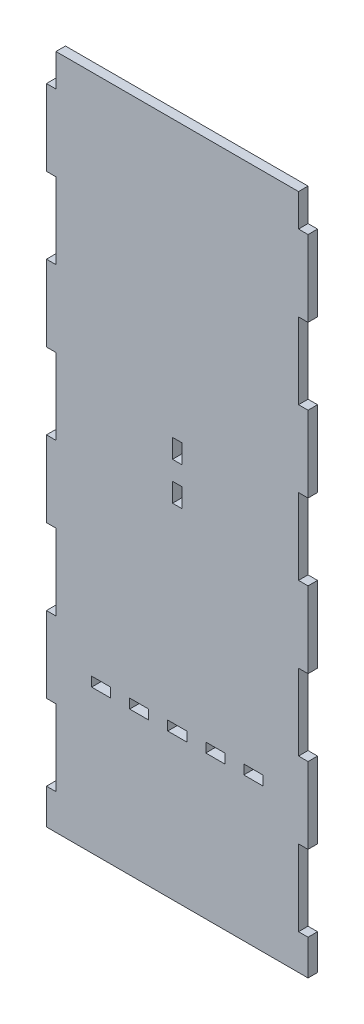
SolidWorks part; units mm, degrees
material "Acrylic (Medium-high impact)"
ref_plane "Front Plane" through (0, 0, 0) normal (0, 0, 1) x (1, 0, 0)
ref_plane "Top Plane" through (0, 0, 0) normal (0, 1, 0) x (1, 0, 0)
ref_plane "Right Plane" through (0, 0, 0) normal (1, 0, 0) x (0, 0, -1)
sketch "Sketch1" plane through (0, 0, 0) normal (0, 0, 1) x (1, 0, 0)
  line L0 (0, 3.175) -> (5.575, 3.175) construction
  line L1 (5.575, 3.175) -> (5.575, 0) construction
  line L2 (5.575, 0) -> (11.925, 0) construction
  line L3 (11.925, 0) -> (11.925, 3.175) construction
  line L4 (11.925, 3.175) -> (18.275, 3.175) construction
  line L5 (18.275, 3.175) -> (18.275, 0) construction
  line L6 (18.275, 0) -> (24.625, 0) construction
  line L7 (0, 3.175) -> (0, 28.575) construction
  line L8 (24.625, 0) -> (24.625, 3.175) construction
  line L9 (24.625, 3.175) -> (30.975, 3.175) construction
  line L10 (30.975, 3.175) -> (30.975, 0) construction
  line L11 (30.975, 0) -> (37.325, 0) construction
  line L12 (37.325, 0) -> (37.325, 3.175) construction
  line L13 (37.325, 3.175) -> (43.675, 3.175) construction
  line L14 (40.5, -996.825) -> (40.5, 49003.175) construction
  line L15 (0, 268.0208) -> (81, 268.0208)
  line L16 (43.675, 0) -> (43.675, 3.175) construction
  line L17 (50.025, 0) -> (43.675, 0) construction
  line L18 (50.025, 3.175) -> (50.025, 0) construction
  line L19 (56.375, 3.175) -> (50.025, 3.175) construction
  line L20 (56.375, 0) -> (56.375, 3.175) construction
  line L21 (81, 3.175) -> (81, 28.575) construction
  line L22 (62.725, 0) -> (56.375, 0) construction
  line L23 (62.725, 3.175) -> (62.725, 0) construction
  line L24 (69.075, 3.175) -> (62.725, 3.175) construction
  line L25 (69.075, 0) -> (69.075, 3.175) construction
  line L26 (75.425, 0) -> (69.075, 0) construction
  line L27 (75.425, 3.175) -> (75.425, 0) construction
  line L28 (81, 3.175) -> (75.425, 3.175) construction
  line L29 (0, 28.575) -> (-3.175, 28.575) construction
  line L30 (-3.175, 28.575) -> (-3.175, 42.175) construction
  line L31 (-3.175, 53.975) -> (0, 53.975)
  line L32 (0, 79.375) -> (-3.175, 79.375)
  line L33 (-3.175, 79.375) -> (-3.175, 104.775)
  line L34 (-3.175, 104.775) -> (0, 104.775)
  line L35 (0, 130.175) -> (-3.175, 130.175)
  line L36 (-3.175, 130.175) -> (-3.175, 155.575)
  line L37 (-3.175, 155.575) -> (0, 155.575)
  line L38 (0, 180.975) -> (-3.175, 180.975)
  line L39 (-3.175, 180.975) -> (-3.175, 206.375)
  line L40 (-3.175, 206.375) -> (0, 206.375)
  line L41 (0, 231.775) -> (-3.175, 231.775)
  line L42 (-3.175, 231.775) -> (-3.175, 257.175)
  line L43 (-3.175, 257.175) -> (0, 257.175)
  line L44 (84.175, 257.175) -> (81, 257.175)
  line L45 (84.175, 231.775) -> (84.175, 257.175)
  line L46 (81, 231.775) -> (84.175, 231.775)
  line L47 (84.175, 206.375) -> (81, 206.375)
  line L48 (84.175, 180.975) -> (84.175, 206.375)
  line L49 (81, 180.975) -> (84.175, 180.975)
  line L50 (84.175, 155.575) -> (81, 155.575)
  line L51 (84.175, 130.175) -> (84.175, 155.575)
  line L52 (81, 130.175) -> (84.175, 130.175)
  line L53 (84.175, 104.775) -> (81, 104.775)
  line L54 (84.175, 79.375) -> (84.175, 104.775)
  line L55 (81, 79.375) -> (84.175, 79.375)
  line L56 (84.175, 53.975) -> (81, 53.975)
  line L57 (84.175, 28.575) -> (84.175, 42.175) construction
  line L58 (81, 28.575) -> (84.175, 28.575) construction
  line L59 (0, 257.175) -> (0, 268.0208)
  line L60 (0, 206.375) -> (0, 231.775)
  line L61 (0, 155.575) -> (0, 180.975)
  line L62 (0, 104.775) -> (0, 130.175)
  line L63 (0, 53.975) -> (0, 79.375)
  line L64 (81, 53.975) -> (81, 79.375)
  line L65 (81, 104.775) -> (81, 130.175)
  line L66 (81, 155.575) -> (81, 180.975)
  line L67 (81, 206.375) -> (81, 231.775)
  line L68 (81, 257.175) -> (81, 268.0208)
  line L69 (50.025, 90.17) -> (56.375, 90.17)
  line L70 (37.325, 93.345) -> (43.675, 93.345)
  line L71 (37.325, 93.345) -> (37.325, 90.17)
  line L72 (37.325, 90.17) -> (43.675, 90.17)
  line L73 (43.675, 93.345) -> (43.675, 90.17)
  line L74 (50.025, 93.345) -> (50.025, 90.17)
  line L75 (50.025, 93.345) -> (56.375, 93.345)
  line L76 (56.375, 93.345) -> (56.375, 90.17)
  line L77 (62.725, 90.17) -> (69.075, 90.17)
  line L78 (62.725, 93.345) -> (62.725, 90.17)
  line L79 (62.725, 93.345) -> (69.075, 93.345)
  line L80 (69.075, 93.345) -> (69.075, 90.17)
  line L81 (24.625, 90.17) -> (30.975, 90.17)
  line L82 (24.625, 93.345) -> (24.625, 90.17)
  line L83 (24.625, 93.345) -> (30.975, 93.345)
  line L84 (30.975, 93.345) -> (30.975, 90.17)
  line L85 (11.925, 90.17) -> (18.275, 90.17)
  line L86 (11.925, 93.345) -> (11.925, 90.17)
  line L87 (11.925, 93.345) -> (18.275, 93.345)
  line L88 (18.275, 93.345) -> (18.275, 90.17)
  line L89 (-3.175, 42.175) -> (84.175, 42.175)
  line L90 (-3.175, 42.175) -> (-3.175, 53.975)
  line L91 (84.175, 42.175) -> (84.175, 53.975)
  line L93 (38.9125, 156.845) -> (42.0875, 156.845)
  line L94 (38.9125, 156.845) -> (38.9125, 163.195)
  line L95 (38.9125, 163.195) -> (42.0875, 163.195)
  line L96 (42.0875, 156.845) -> (42.0875, 163.195)
  line L97 (38.9125, 169.545) -> (42.0875, 169.545)
  line L98 (38.9125, 169.545) -> (38.9125, 175.895)
  line L99 (38.9125, 175.895) -> (42.0875, 175.895)
  line L100 (42.0875, 169.545) -> (42.0875, 175.895)
  point P20 (40.5, 268.0208)
  point P21 (40.5, 3.175)
  dimension "D1" = 3.175
  dimension "D2" = 6.35
  dimension "D3" = 3.175
  dimension "D4" = 40.5
  dimension "D5" = 42.175
  dimension "D6" = 25.4
  dimension "D7" = 225.8458
  dimension "D8" = 3.175
  dimension "D10" = 25.4
  dimension "D11" = 6.35
  dimension "D12" = 3.175
  dimension "D13" = 3.175
  dimension "D14" = 90.17
  dimension "D17" = 6.35
  dimension "D18" = 6.35
  dimension "D19" = 6.35
  dimension "D20" = 13.6
  dimension "D21" = 1.5875
  dimension "D22" = 63.5
  dimension "D9" = 5
  dimension "D15" = 3
  dimension "D16" = 3
extrude "Boss-Extrude1" add sketch "Sketch1" along normal blind 3.175
